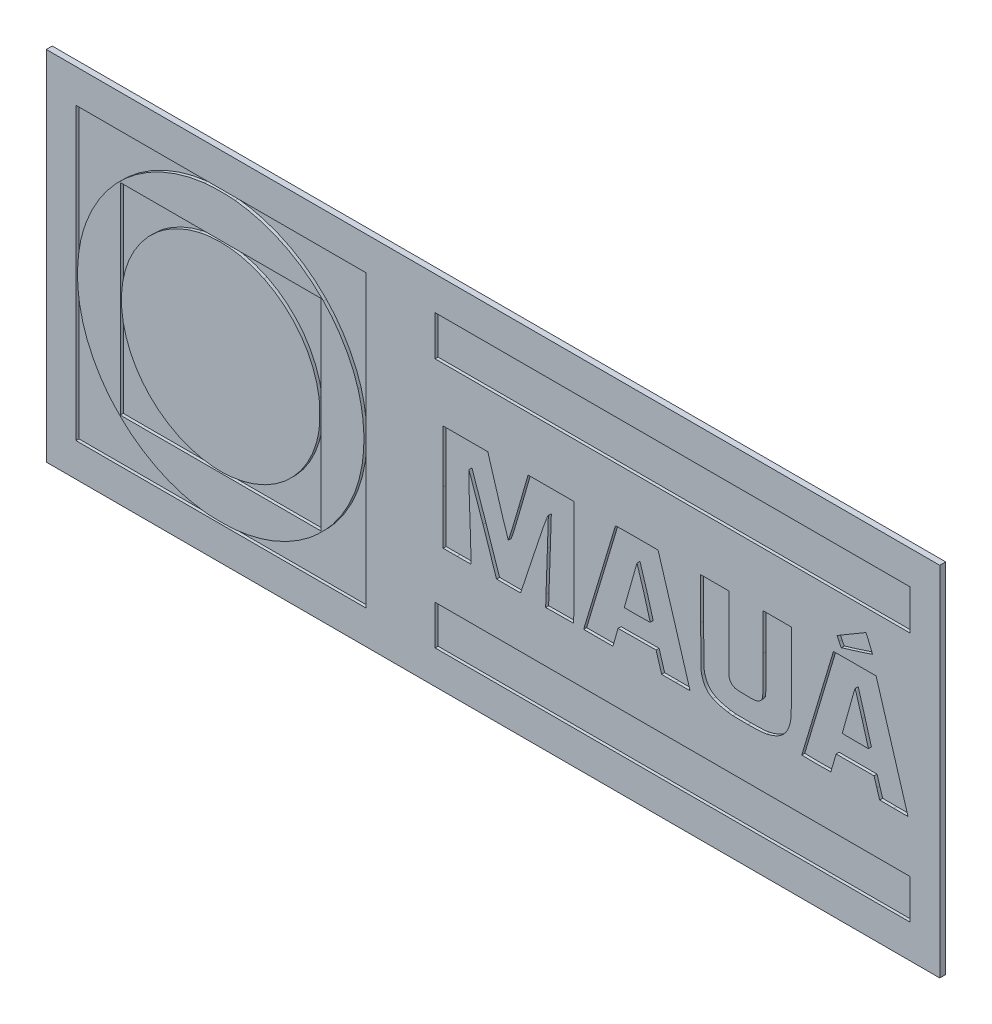
SolidWorks part; units mm, degrees
ref_plane "Front Plane" through (0, 0, 0) normal (0, 0, 1) x (1, 0, 0)
ref_plane "Top Plane" through (0, 0, 0) normal (0, 1, 0) x (1, 0, 0)
ref_plane "Right Plane" through (0, 0, 0) normal (1, 0, 0) x (0, 0, -1)
sketch "Model" plane through (0, 0, 0) normal (0, 0, 1) x (1, 0, 0)
  line L0 (-69.9995, 0.0001) -> (-69.9995, 24.3737)
  line L1 (-69.9995, 24.3737) -> (-45.6654, 24.3737)
  line L2 (-45.6654, 24.3737) -> (-21.3314, 24.3737)
  line L3 (-21.3314, 24.3737) -> (-21.3314, 0.0001)
  line L4 (-21.3314, 0.0001) -> (-21.3314, -24.3735)
  line L5 (-21.3314, -24.3735) -> (-45.6654, -24.3735)
  line L6 (-45.6654, -24.3735) -> (-69.9995, -24.3735)
  line L7 (-69.9995, -24.3735) -> (-69.9995, 0.0001)
  line L8 (-62.5729, -0.0394) -> (-62.5729, 16.868)
  line L9 (-62.5729, 16.868) -> (-45.7049, 16.868)
  line L10 (-45.7049, 16.868) -> (-28.837, 16.868)
  line L11 (-28.837, 16.868) -> (-28.837, -0.0394)
  line L12 (-28.837, -0.0394) -> (-28.837, -16.9468)
  line L13 (-28.837, -16.9468) -> (-45.7049, -16.9468)
  line L14 (-45.7049, -16.9468) -> (-62.5729, -16.9468)
  line L15 (-62.5729, -16.9468) -> (-62.5729, -0.0394)
  line L16 (-44.0734, -16.6275) -> (-44.0739, -16.6275)
  line L17 (-9.7174, -21.0552) -> (-9.7174, -17.7369)
  line L18 (-9.7174, -17.7369) -> (30.1415, -17.7369)
  line L19 (30.1415, -17.7369) -> (70.0004, -17.7369)
  line L20 (70.0004, -17.7369) -> (70.0004, -21.0552)
  line L21 (70.0004, -21.0552) -> (70.0004, -24.3735)
  line L22 (70.0004, -24.3735) -> (30.1415, -24.3735)
  line L23 (30.1415, -24.3735) -> (-9.7174, -24.3735)
  line L24 (-9.7174, -24.3735) -> (-9.7174, -21.0552)
  line L25 (34.8609, 1.6) -> (34.8353, 8.5723)
  line L26 (34.8353, 8.5723) -> (37.209, 8.5723)
  line L27 (37.209, 8.5723) -> (39.5828, 8.5723)
  line L28 (39.5828, 8.5723) -> (39.5828, 2.3821)
  line L29 (45.3499, 2.3901) -> (45.3501, 8.5723)
  line L30 (45.3501, 8.5723) -> (47.7203, 8.5723)
  line L31 (47.7203, 8.5723) -> (50.0905, 8.5723)
  line L32 (50.0905, 8.5723) -> (50.0905, 2.1041)
  line L33 (40.2937, -9.2369) -> (40.2939, -9.2373)
  line L34 (-8.3743, -0.3159) -> (-8.3743, 8.5723)
  line L35 (-8.3743, 8.5723) -> (-4.6252, 8.5723)
  line L36 (-4.6252, 8.5723) -> (-0.8761, 8.5723)
  line L37 (-0.8761, 8.5723) -> (-0.7166, 8.039)
  line L38 (4.2718, 3.0024) -> (5.883, 8.5723)
  line L39 (5.883, 8.5723) -> (9.7366, 8.5723)
  line L40 (9.7366, 8.5723) -> (13.5903, 8.5723)
  line L41 (13.5903, 8.5723) -> (13.5702, -0.2962)
  line L42 (13.5702, -0.2962) -> (13.5502, -9.1647)
  line L43 (13.5502, -9.1647) -> (11.1931, -9.1856)
  line L44 (11.1931, -9.1856) -> (8.8361, -9.2064)
  line L45 (8.8361, -9.2064) -> (8.8974, -7.2498)
  line L46 (6.875, -2.4095) -> (4.6308, -9.2041)
  line L47 (4.6308, -9.2041) -> (2.6119, -9.2031)
  line L48 (2.6119, -9.2031) -> (0.593, -9.2021)
  line L49 (0.593, -9.2021) -> (-1.6879, -2.4083)
  line L50 (-6.0304, -9.2038) -> (-8.3742, -9.2038)
  line L51 (-8.3742, -9.2038) -> (-8.3743, -0.3159)
  line L52 (24.1504, 8.5723) -> (27.706, 8.5723)
  line L53 (27.706, 8.5723) -> (30.4035, -0.2912)
  line L54 (30.6795, -9.2042) -> (28.3074, -9.2042)
  line L55 (28.3074, -9.2042) -> (27.8418, -7.6634)
  line L56 (27.8418, -7.6634) -> (27.3763, -6.1227)
  line L57 (27.3763, -6.1227) -> (24.1845, -6.1425)
  line L58 (24.1845, -6.1425) -> (20.9927, -6.1624)
  line L59 (20.9927, -6.1624) -> (20.5589, -7.6833)
  line L60 (20.5589, -7.6833) -> (20.1251, -9.2042)
  line L61 (20.1251, -9.2042) -> (17.677, -9.2042)
  line L62 (17.677, -9.2042) -> (15.229, -9.2042)
  line L63 (15.229, -9.2042) -> (15.2757, -8.9869)
  line L64 (60.7407, 8.5723) -> (64.3065, 8.5723)
  line L65 (64.3065, 8.5723) -> (64.5817, 7.6835)
  line L66 (67.2674, -9.1857) -> (64.9055, -9.1647)
  line L67 (64.9055, -9.1647) -> (64.4375, -7.6438)
  line L68 (64.4375, -7.6438) -> (63.9694, -6.123)
  line L69 (63.9694, -6.123) -> (60.7862, -6.123)
  line L70 (60.7862, -6.123) -> (57.603, -6.123)
  line L71 (57.603, -6.123) -> (57.4465, -6.6562)
  line L72 (51.8289, -9.1679) -> (51.8289, -9.1681)
  line L73 (60.8179, -2.6466) -> (63.0293, -2.6466)
  line L74 (63.0293, -2.6466) -> (61.9367, 1.1546)
  line L75 (58.0914, 10.4692) -> (57.7662, 11.1811)
  line L76 (57.7662, 11.1811) -> (59.0836, 11.9588)
  line L77 (-9.7174, 21.0159) -> (-9.7174, 24.3737)
  line L78 (-9.7174, 24.3737) -> (30.1415, 24.3737)
  line L79 (30.1415, 24.3737) -> (70.0004, 24.3737)
  line L80 (70.0004, 24.3737) -> (70.0004, 21.0159)
  line L81 (70.0004, 21.0159) -> (70.0004, 17.6581)
  line L82 (70.0004, 17.6581) -> (30.1415, 17.6581)
  line L83 (30.1415, 17.6581) -> (-9.7174, 17.6581)
  line L84 (-9.7174, 17.6581) -> (-9.7174, 21.0159)
  spline S0 degree 3 poles (-43.4419, -23.9765) (-38.7371, -23.5117) (-34.4106, -21.7505) (-30.6828, -18.7826) knots 0 0 0 0 1 1 1 1
  spline S1 degree 3 poles (-30.6828, -18.7826) (-29.6153, -17.9328) (-27.8115, -16.1357) (-26.9779, -15.0917) knots 0 0 0 0 1 1 1 1
  spline S2 degree 3 poles (-26.9779, -15.0917) (-22.0165, -8.8776) (-20.4277, -0.8522) (-22.6469, 6.7854) knots 0 0 0 0 1 1 1 1
  spline S3 degree 3 poles (-22.6469, 6.7854) (-23.6796, 10.3395) (-25.7762, 13.9064) (-28.4673, 16.6872) knots 0 0 0 0 1 1 1 1
  spline S4 degree 3 poles (-28.4673, 16.6872) (-32.4189, 20.7705) (-37.5605, 23.2737) (-43.2952, 23.9064) knots 0 0 0 0 1 1 1 1
  spline S5 degree 3 poles (-43.2952, 23.9064) (-44.513, 24.0408) (-47.1601, 24.0185) (-48.4702, 23.863) knots 0 0 0 0 1 1 1 1
  spline S6 degree 3 poles (-48.4702, 23.863) (-55.7554, 22.9979) (-62.2041, 18.9018) (-66.1368, 12.6412) knots 0 0 0 0 1 1 1 1
  spline S7 degree 3 poles (-66.1368, 12.6412) (-67.5474, 10.3956) (-68.6351, 7.7541) (-69.211, 5.1751) knots 0 0 0 0 1 1 1 1
  spline S8 degree 3 poles (-69.211, 5.1751) (-69.8519, 2.3048) (-69.9357, -1.1468) (-69.4352, -4.0687) knots 0 0 0 0 1 1 1 1
  spline S9 degree 3 poles (-69.4352, -4.0687) (-68.7556, -8.037) (-67.0745, -11.7812) (-64.5293, -14.9952) knots 0 0 0 0 1 1 1 1
  spline S10 degree 3 poles (-64.5293, -14.9952) (-63.7308, -16.0035) (-61.7474, -17.9923) (-60.7557, -18.7792) knots 0 0 0 0 1 1 1 1
  spline S11 degree 3 poles (-60.7557, -18.7792) (-57.1789, -21.6171) (-52.9523, -23.4052) (-48.6677, -23.893) knots 0 0 0 0 1 1 1 1
  spline S12 degree 3 poles (-48.6677, -23.893) (-48.2549, -23.94) (-47.8105, -23.9909) (-47.6801, -24.0061) knots 0 0 0 0 1 1 1 1
  spline S13 degree 3 poles (-47.6801, -24.0061) (-47.1222, -24.0711) (-44.1923, -24.0507) (-43.4419, -23.9765) knots 0 0 0 0 1 1 1 1
  spline S14 degree 3 poles (-44.0739, -16.6275) (-36.4624, -15.8616) (-30.251, -9.8949) (-29.1968, -2.3363) knots 0 0 0 0 1 1 1 1
  spline S15 degree 3 poles (-29.1968, -2.3363) (-29.0394, -1.2078) (-29.0372, 1.1432) (-29.1922, 2.2363) knots 0 0 0 0 1 1 1 1
  spline S16 degree 3 poles (-29.1922, 2.2363) (-29.978, 7.7647) (-33.412, 12.4832) (-38.4358, 14.9377) knots 0 0 0 0 1 1 1 1
  spline S17 degree 3 poles (-38.4358, 14.9377) (-41.8346, 16.5982) (-45.6084, 17.047) (-49.3388, 16.2344) knots 0 0 0 0 1 1 1 1
  spline S18 degree 3 poles (-49.3388, 16.2344) (-51.74, 15.7114) (-54.4185, 14.3961) (-56.3229, 12.8049) knots 0 0 0 0 1 1 1 1
  spline S19 degree 3 poles (-56.3229, 12.8049) (-63.8164, 6.544) (-64.4521, -4.5596) (-57.7182, -11.5653) knots 0 0 0 0 1 1 1 1
  spline S20 degree 3 poles (-57.7182, -11.5653) (-54.1732, -15.2534) (-49.1049, -17.1337) (-44.0734, -16.6275) knots 0 0 0 0 1 1 1 1
  spline S21 degree 3 poles (40.2939, -9.2373) (40.1852, -9.2193) (39.7764, -9.1649) (39.3853, -9.1164) knots 0 0 0 0 1 1 1 1
  spline S22 degree 3 poles (39.3853, -9.1164) (38.5074, -9.0075) (37.5162, -8.7269) (36.8863, -8.4089) knots 0 0 0 0 1 1 1 1
  spline S23 degree 3 poles (36.8863, -8.4089) (35.9422, -7.9323) (35.4066, -7.2228) (35.0601, -5.9897) knots 0 0 0 0 1 1 1 1
  spline S24 degree 3 poles (35.0601, -5.9897) (34.8884, -5.3787) (34.8863, -5.3001) (34.8609, 1.6) knots 0 0 0 0 1 1 1 1
  spline S25 degree 3 poles (39.5828, 2.3821) (39.5828, -2.0842) (39.6082, -3.8829) (39.6739, -4.0767) knots 0 0 0 0 1 1 1 1
  spline S26 degree 3 poles (39.6739, -4.0767) (39.8208, -4.5098) (40.0331, -4.7541) (40.4327, -4.9498) knots 0 0 0 0 1 1 1 1
  spline S27 degree 3 poles (40.4327, -4.9498) (40.7769, -5.1183) (40.9305, -5.1356) (42.3193, -5.1623) knots 0 0 0 0 1 1 1 1
  spline S28 degree 3 poles (42.3193, -5.1623) (43.5366, -5.1856) (43.916, -5.1669) (44.2664, -5.0648) knots 0 0 0 0 1 1 1 1
  spline S29 degree 3 poles (44.2664, -5.0648) (44.769, -4.9187) (45.1358, -4.5614) (45.2666, -4.0907) knots 0 0 0 0 1 1 1 1
  spline S30 degree 3 poles (45.2666, -4.0907) (45.3212, -3.8942) (45.3496, -1.6802) (45.3499, 2.3901) knots 0 0 0 0 1 1 1 1
  spline S31 degree 3 poles (50.0905, 2.1041) (50.0905, -3.2947) (50.071, -4.4766) (49.9719, -5.0446) knots 0 0 0 0 1 1 1 1
  spline S32 degree 3 poles (49.9719, -5.0446) (49.5701, -7.3485) (48.3989, -8.5124) (45.9414, -9.0499) knots 0 0 0 0 1 1 1 1
  spline S33 degree 3 poles (45.9414, -9.0499) (45.2491, -9.2013) (44.8676, -9.2253) (42.8219, -9.2462) knots 0 0 0 0 1 1 1 1
  spline S34 degree 3 poles (42.8219, -9.2462) (41.54, -9.2593) (40.4024, -9.2556) (40.2937, -9.2369) knots 0 0 0 0 1 1 1 1
  spline S35 degree 3 poles (-0.7166, 8.039) (1.2606, 1.4299) (2.4997, -2.5676) (2.5712, -2.5676) knots 0 0 0 0 1 1 1 1
  spline S36 degree 3 poles (2.5712, -2.5676) (2.6218, -2.5676) (3.3613, -0.1454) (4.2718, 3.0024) knots 0 0 0 0 1 1 1 1
  spline S37 degree 3 poles (8.8974, -7.2498) (8.9312, -6.1737) (9.0364, -3.1245) (9.1314, -0.4738) knots 0 0 0 0 1 1 1 1
  spline S38 degree 3 poles (9.1314, -0.4738) (9.2263, 2.1768) (9.2965, 4.3545) (9.2873, 4.3653) knots 0 0 0 0 1 1 1 1
  spline S39 degree 3 poles (9.2873, 4.3653) (9.1811, 4.4909) (8.8082, 3.4435) (6.875, -2.4095) knots 0 0 0 0 1 1 1 1
  spline S40 degree 3 poles (-1.6879, -2.4083) (-2.9425, 1.3282) (-4.0024, 4.3854) (-4.0434, 4.3854) knots 0 0 0 0 1 1 1 1
  spline S41 degree 3 poles (-4.0434, 4.3854) (-4.1232, 4.3854) (-4.1124, 3.9716) (-3.8217, -4.1855) knots 0 0 0 0 1 1 1 1
  spline S42 degree 3 poles (-3.8217, -4.1855) (-3.7242, -6.9223) (-3.6538, -9.1711) (-3.6654, -9.1827) knots 0 0 0 0 1 1 1 1
  spline S43 degree 3 poles (-3.6654, -9.1827) (-3.677, -9.1942) (-4.7412, -9.2038) (-6.0304, -9.2038) knots 0 0 0 0 1 1 1 1
  spline S44 degree 3 poles (15.2757, -8.9869) (15.3472, -8.6537) (20.5172, 8.4947) (20.5585, 8.536) knots 0 0 0 0 1 1 1 1
  spline S45 degree 3 poles (20.5585, 8.536) (20.5785, 8.556) (22.1949, 8.5723) (24.1504, 8.5723) knots 0 0 0 0 1 1 1 1
  spline S46 degree 3 poles (30.4035, -0.2912) (31.8872, -5.1661) (33.0899, -9.1659) (33.0763, -9.1795) knots 0 0 0 0 1 1 1 1
  spline S47 degree 3 poles (33.0763, -9.1795) (33.0627, -9.1931) (31.9842, -9.2042) (30.6795, -9.2042) knots 0 0 0 0 1 1 1 1
  spline S48 degree 3 poles (26.3887, -2.5874) (26.3887, -2.3697) (24.2099, 4.9941) (24.1684, 4.9167) knots 0 0 0 0 1 1 1 1
  spline S49 degree 3 poles (24.1684, 4.9167) (24.1192, 4.8249) (22.0433, -2.5254) (22.0433, -2.6079) knots 0 0 0 0 1 1 1 1
  spline S50 degree 3 poles (22.0433, -2.6079) (22.0433, -2.6292) (23.021, -2.6466) (24.216, -2.6466) knots 0 0 0 0 1 1 1 1
  spline S51 degree 3 poles (24.216, -2.6466) (25.411, -2.6466) (26.3887, -2.62) (26.3887, -2.5874) knots 0 0 0 0 1 1 1 1
  spline S52 degree 3 poles (51.8289, -9.1681) (51.8289, -9.0973) (57.1136, 8.511) (57.144, 8.5413) knots 0 0 0 0 1 1 1 1
  spline S53 degree 3 poles (57.144, 8.5413) (57.161, 8.5584) (58.7796, 8.5723) (60.7407, 8.5723) knots 0 0 0 0 1 1 1 1
  spline S54 degree 3 poles (64.5817, 7.6835) (65.9484, 3.2691) (69.6916, -9.1444) (69.6642, -9.1717) knots 0 0 0 0 1 1 1 1
  spline S55 degree 3 poles (69.6642, -9.1717) (69.645, -9.1909) (68.5665, -9.1972) (67.2674, -9.1857) knots 0 0 0 0 1 1 1 1
  spline S56 degree 3 poles (57.4465, -6.6562) (57.3604, -6.9496) (57.1641, -7.6302) (57.0103, -8.1689) knots 0 0 0 0 1 1 1 1
  spline S57 degree 3 poles (57.0103, -8.1689) (56.8564, -8.7075) (56.718, -9.1608) (56.7026, -9.1762) knots 0 0 0 0 1 1 1 1
  spline S58 degree 3 poles (56.7026, -9.1762) (56.6608, -9.218) (51.8289, -9.2101) (51.8289, -9.1679) knots 0 0 0 0 1 1 1 1
  spline S59 degree 3 poles (61.9367, 1.1546) (61.3358, 3.2453) (60.8277, 4.9723) (60.8077, 4.9923) knots 0 0 0 0 1 1 1 1
  spline S60 degree 3 poles (60.8077, 4.9923) (60.7654, 5.0346) (60.8066, 5.176) (59.6066, 0.8692) knots 0 0 0 0 1 1 1 1
  spline S61 degree 3 poles (59.6066, 0.8692) (59.0981, -0.9559) (58.665, -2.4936) (58.6443, -2.5479) knots 0 0 0 0 1 1 1 1
  spline S62 degree 3 poles (58.6443, -2.5479) (58.6146, -2.6254) (59.0813, -2.6466) (60.8179, -2.6466) knots 0 0 0 0 1 1 1 1
  spline S63 degree 3 poles (59.0836, 11.9588) (62.2371, 13.8204) (62.5951, 14.0284) (62.6086, 14.0069) knots 0 0 0 0 1 1 1 1
  spline S64 degree 3 poles (62.6086, 14.0069) (62.771, 13.7503) (63.7366, 11.4435) (63.6966, 11.4079) knots 0 0 0 0 1 1 1 1
  spline S65 degree 3 poles (63.6966, 11.4079) (63.6397, 11.3572) (58.5761, 9.7574) (58.4725, 9.7574) knots 0 0 0 0 1 1 1 1
  spline S66 degree 3 poles (58.4725, 9.7574) (58.4417, 9.7574) (58.2702, 10.0777) (58.0914, 10.4692) knots 0 0 0 0 1 1 1 1
sketch "Sketch2" plane through (0, 0, 0) normal (0, 0, 1) x (1, 0, 0)
  line L1 (75, -30) -> (-75, -30)
  line L2 (75, -30) -> (75, 30)
  line L3 (75, 30) -> (-75, 30)
  line L4 (-75, -30) -> (-75, 30)
  line L5 (75, -30) -> (-75, 30) construction
  line L6 (75, 30) -> (-75, -30) construction
  point P0 (0, 0)
  dimension "D1" = 150
  dimension "D2" = 60
extrude "Boss-Extrude1" add sketch "Sketch2" against normal blind 1
extrude "Cut-Extrude1" cut sketch "Model" against normal blind 0.5 contours L84 L83 L82 L81 L80 L79 L78 L77 | L7 L6 L5 L4 L3 L2 L1 L0 S13 S12 S11 S10 S9 S8 S7 S6 S5 S4 S3 S2 S1 S0 | L15 L14 L13 L12 L11 L10 L9 L8 S20 S19 S18 S17 S16 S15 S14 L16 | L24 L23 L22 L21 L20 L19 L18 L17 | S43 S42 S41 S40 L49 L48 L47 L46 S39 S38 S37 L45 L44 L43 L42 L41 L40 L39 L38 S36 S35 L37 L36 L35 L34 L51 L50 | S47 S46 L53 L52 S45 S44 L63 L62 L61 L60 L59 L58 L57 L56 L55 L54 S51 S50 S49 S48 | S34 S33 S32 S31 L32 L31 L30 L29 S30 S29 S28 S27 S26 S25 L28 L27 L26 L25 S24 S23 S22 S21 L33 | S58 S57 S56 L71 L70 L69 L68 L67 L66 S55 S54 L65 L64 S53 S52 S62 S61 S60 S59 L74 L73 | S66 S65 S64 S63 L76 L75
